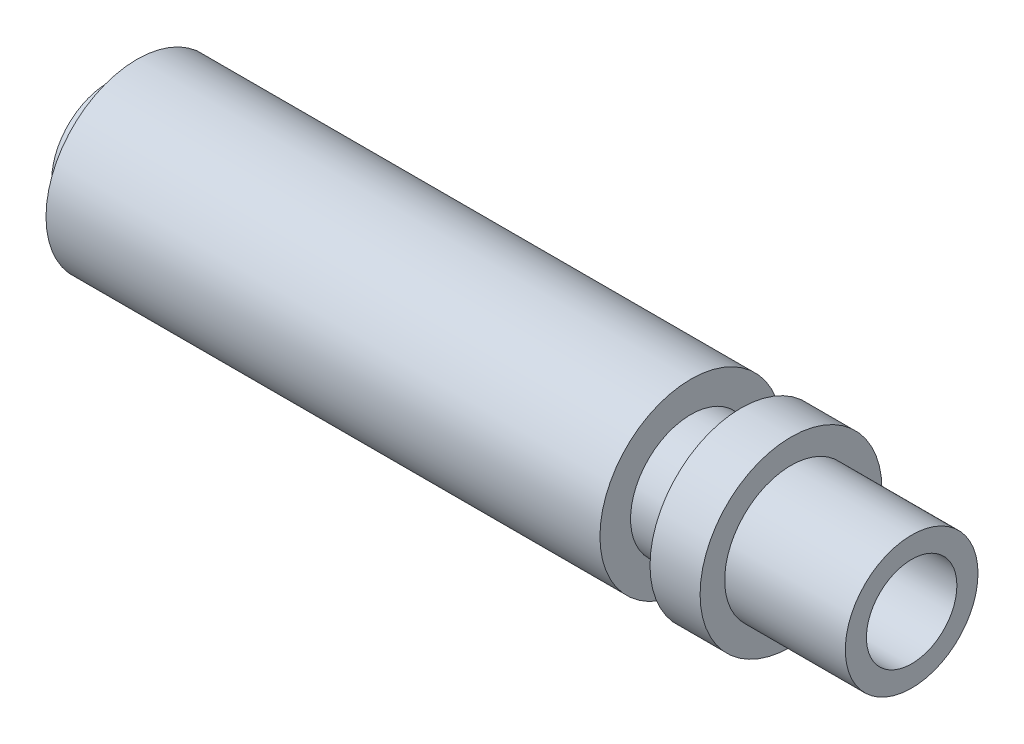
SolidWorks part; units mm, degrees
ref_plane "Front Plane" through (0, 0, 0) normal (0, 0, 1) x (1, 0, 0)
ref_plane "Top Plane" through (0, 0, 0) normal (0, 1, 0) x (1, 0, 0)
ref_plane "Right Plane" through (0, 0, 0) normal (1, 0, 0) x (0, 0, -1)
sketch "Sketch1" plane through (0, 0, 0) normal (1, 0, 0) x (0, 0, -1)
  circle A0 centre (0, 0) radius 15.0762
  dimension "D1" = 30.1523
extrude "Boss-Extrude1" add sketch "Sketch1" along normal blind 108.4446
sketch "Sketch2" plane through (0, 0, 0) normal (-1, 0, 0) x (0, 0, 1)
  circle A0 centre (0, 0) radius 4.5847
  circle A1 centre (0, 0) radius 9.3853
  dimension "D1" = 18.7706
  dimension "D2" = 9.1694
extrude "Boss-Extrude2" add sketch "Sketch2" along normal blind 4.7498
sketch "Sketch3" plane through (108.4446, 0, 0) normal (1, 0, 0) x (0, 0, -1)
  circle A0 centre (0, 0) radius 7.5
  dimension "D1" = 15
extrude "Cut-Extrude1" cut sketch "Sketch3" against normal blind 18.75
sketch "Sketch4" plane through (108.4446, 0, 0) normal (1, 0, 0) x (0, 0, -1)
  circle A0 centre (0, 0) radius 11
  circle A1 centre (0, 0) radius 7.5
  circle A2 centre (0, 0) radius 7.5 construction
  dimension "D1" = 22
extrude "Boss-Extrude3" add sketch "Sketch4" along normal blind 20
ref_plane "Plane1" through (100.1423, 0, 0) normal (1, 0, 0) x (0, 0, -1)
sketch "Sketch5" plane through (100.1423, 0, 0) normal (1, 0, 0) x (0, 0, -1)
  circle A1 centre (0, 0) radius 15.0762
  circle A2 centre (0, 0) radius 15.0762 construction
  circle A4 centre (0, 0) radius 10
  dimension "D1" = 20
extrude "Cut-Extrude4" cut sketch "Sketch5" against normal blind 8.3024
